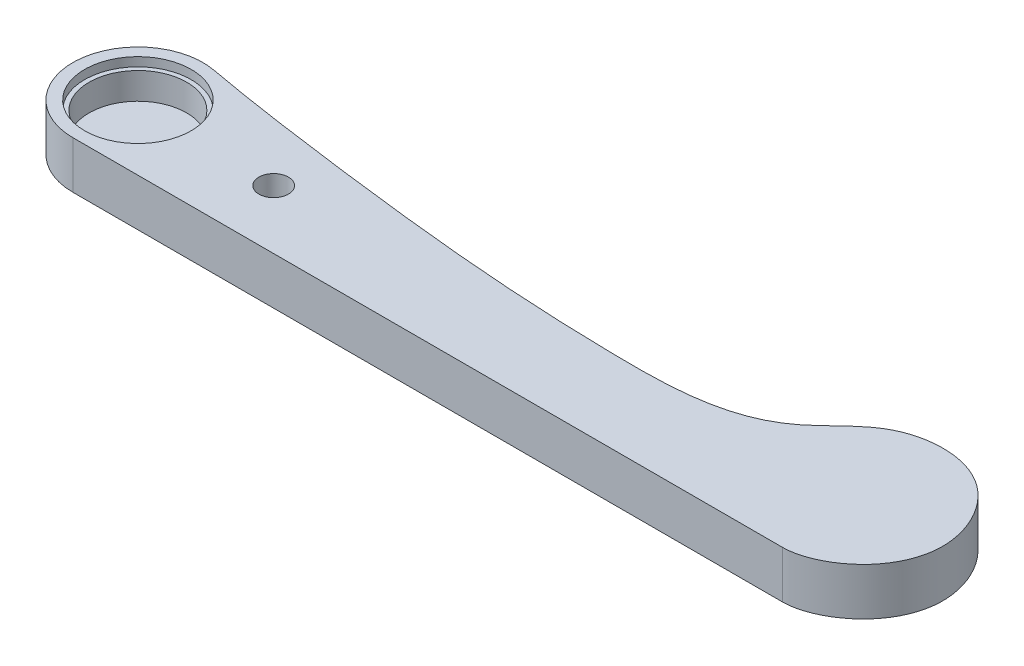
SolidWorks part; units mm, degrees
ref_plane "Front Plane" through (0, 0, 0) normal (0, 0, 1) x (1, 0, 0)
ref_plane "Top Plane" through (0, 0, 0) normal (0, 1, 0) x (1, 0, 0)
ref_plane "Right Plane" through (0, 0, 0) normal (1, 0, 0) x (0, 0, -1)
sketch "Sketch1" plane through (0, 0, 0) normal (0, 1, 0) x (1, 0, 0)
  line L1 (0, -11) -> (120, -11)
  arc A0 (2.0465, 10.808) -> (0, -11) centre (0, 0) ccw
  spline S0 degree 3 poles (2.0465, 10.808) (9.7359, 9.352) (39.0519, 5.2296) (69.6619, 2.5328) (100.6045, 3.1678) (111.4451, 17.4753) (127.8738, 17.9483) (135.5652, 3.4707) (129.9951, -7.6741) (123.0304, -11) (120, -11) knots 0 0 0 0 0.184805 0.470871 0.627246 0.69646 0.785065 0.878194 0.938783 1 1 1 1
  dimension "D1" = 11
  dimension "D2" = 120
  dimension "D3" = 9.0692
  dimension "D4" = 4.2758
  dimension "D5" = 14
  dimension "D6" = 7.2244
  dimension "D7" = 14.4047
  dimension "D8" = 8.6557
  dimension "D9" = 24.91
  dimension "D10" = 4.0983
  dimension "D11" = 8.8735
  dimension "D12" = 13.3055
  dimension "D13" = 7.1897
  dimension "D14" = 5.0776
extrude "Boss-Extrude1" add sketch "Sketch1" along normal blind 8
sketch "Sketch2" plane through (0, 8, 0) normal (0, 1, 0) x (1, 0, 0)
  circle A0 centre (0, 0) radius 9
  dimension "D1" = 18
extrude "Cut-Extrude1" cut sketch "Sketch2" against normal blind 1.5
sketch "Sketch3" plane through (0, 6.5, 0) normal (0, 1, 0) x (1, 0, 0)
  circle A0 centre (0, 0) radius 8.25
  dimension "D1" = 16.5
extrude "Cut-Extrude2" cut sketch "Sketch3" against normal blind 4.5
sketch "Sketch4" plane through (0, 0, 0) normal (0, -1, 0) x (1, 0, 0)
  line L0 (0, 0) -> (141.2749, 6.1682) construction
  line L1 (0, 11) -> (120, 11) construction
  circle A0 centre (24, 1.0479) radius 2.5
  dimension "D2" = 5
  dimension "D1" = 24
  dimension "D3" = 2.5
extrude "Cut-Extrude3" cut sketch "Sketch4" against normal up to next
